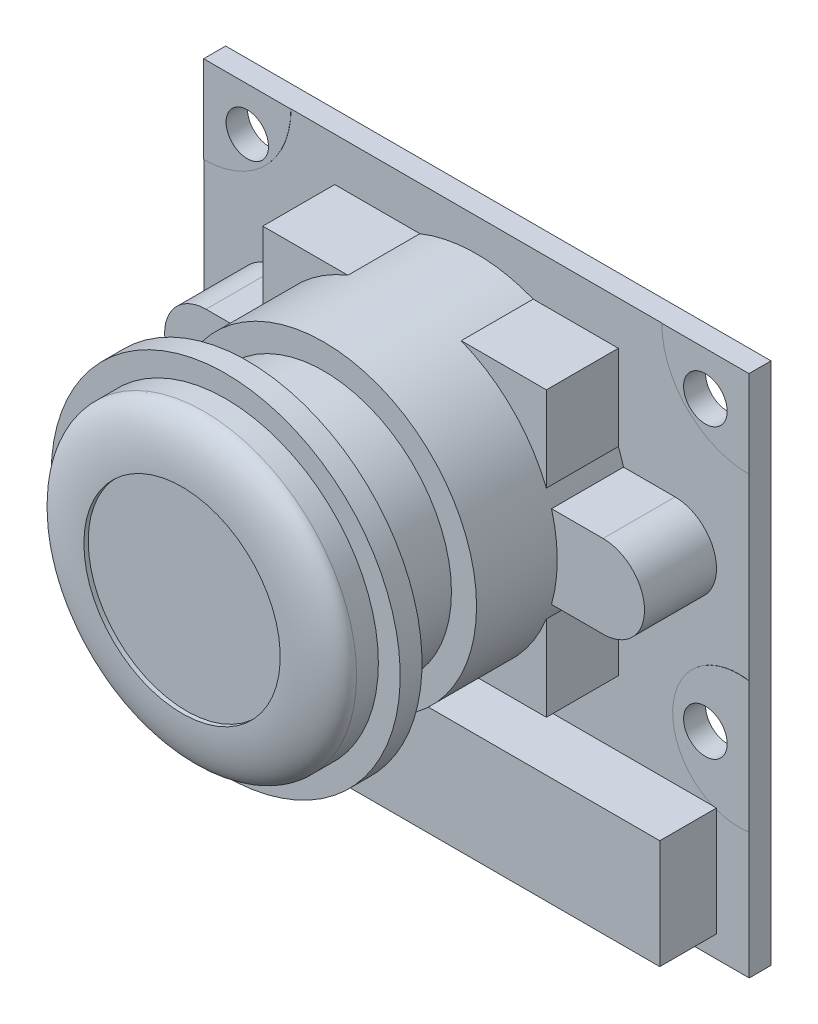
SolidWorks part; units mm, degrees
ref_plane "Alzado" through (0, 0, 0) normal (0, 0, 1) x (1, 0, 0)
ref_plane "Planta" through (0, 0, 0) normal (0, 1, 0) x (1, 0, 0)
ref_plane "Vista lateral" through (0, 0, 0) normal (1, 0, 0) x (0, 0, -1)
sketch "Croquis1" plane through (0, 0, 0) normal (0, 0, 1) x (1, 0, 0)
  line L1 (12.5, 12) -> (-12.5, 12)
  line L2 (12.5, 12) -> (12.5, -12)
  line L3 (12.5, -12) -> (-12.5, -12)
  line L4 (-12.5, 12) -> (-12.5, -12)
  line L5 (12.5, 12) -> (-12.5, -12) construction
  line L6 (12.5, -12) -> (-12.5, 12) construction
  point P0 (0, 0)
  dimension "D1" = 25
  dimension "D2" = 24
extrude "Saliente-Extruir1" add sketch "Croquis1" along normal blind 1
sketch "Croquis2" plane through (0, 0, 1) normal (0, 0, 1) x (1, 0, 0)
  line L0 (-12.5, -12) -> (12.5, -12) construction
  line L1 (11, -6) -> (-11, -6)
  line L2 (11, -6) -> (11, -11)
  line L3 (11, -11) -> (-11, -11)
  line L4 (-11, -6) -> (-11, -11)
  line L5 (11, -6) -> (-11, -11) construction
  line L6 (11, -11) -> (-11, -6) construction
  point P0 (0, -8.5)
  dimension "D1" = 22
  dimension "D2" = 5
  dimension "D3" = 1
extrude "Saliente-Extruir2" add sketch "Croquis2" along normal blind 2.6
sketch "Croquis3" plane through (0, 0, 1) normal (0, 0, 1) x (1, 0, 0)
  line L0 (-9.1, 5.4) -> (-6.5, 5.4)
  line L1 (-6.5, -3) -> (6.5, -3)
  line L2 (-6.5, -3) -> (-6.5, 1.6)
  line L3 (-6.5, 10) -> (6.5, 10)
  line L4 (6.5, -3) -> (6.5, 1.6)
  line L5 (-6.5, -3) -> (6.5, 10) construction
  line L6 (-6.5, 10) -> (6.5, -3) construction
  line L7 (-6.5, 5.4) -> (-6.5, 10)
  line L8 (6.5, 5.4) -> (9.1, 5.4)
  line L9 (6.5, 5.4) -> (6.5, 10)
  line L10 (9.1, 1.6) -> (6.5, 1.6)
  line L11 (12.5, 12) -> (-12.5, 12) construction
  line L12 (-6.5, 1.6) -> (-9.1, 1.6)
  arc A0 (-9.1, 5.4) -> (-9.1, 1.6) centre (-9.1, 3.5) ccw
  arc A1 (9.1, 1.6) -> (9.1, 5.4) centre (9.1, 3.5) ccw
  point P3 (-11, 3.5)
  point P4 (0, 3.5)
  point P19 (11, 3.5)
  dimension "D1" = 22
  dimension "D2" = 3.8
  dimension "D3" = 13
  dimension "D4" = 13
  dimension "D5" = 2
extrude "Saliente-Extruir3" add sketch "Croquis3" along normal blind 3.3
sketch "Croquis5" plane through (0, 0, 1) normal (0, 0, 1) x (1, 0, 0)
  line L0 (-11, 3.5) -> (11, 3.5) construction
  arc A0 (-9.1, 5.4) -> (-9.1, 1.6) centre (-9.1, 3.5) ccw construction
  arc A1 (9.1, 1.6) -> (9.1, 5.4) centre (9.1, 3.5) ccw construction
  circle A2 centre (0, 3.5) radius 7
  dimension "D1" = 14
extrude "Saliente-Extruir4" add sketch "Croquis5" along normal blind 7
sketch "Croquis6" plane through (0, 0, 8) normal (0, 0, 1) x (1, 0, 0)
  circle A0 centre (0, 3.5) radius 5.85
  dimension "D1" = 11.7
extrude "Saliente-Extruir5" add sketch "Croquis6" along normal blind 3.5
sketch "Croquis7" plane through (0, 0, 11.5) normal (0, 0, 1) x (1, 0, 0)
  point P0 (0, 3.5)
ref_plane "Plano1" through (0, 3.5, 0) normal (0, -1, 0) x (-1, 0, 0)
sketch "Croquis8" plane through (0, 3.5, 0) normal (0, -1, 0) x (-1, 0, 0)
  line L0 (0, -11.5) -> (-8, -11.5)
  line L1 (-5.85, -11.5) -> (5.85, -11.5) construction
  line L2 (-8, -11.5) -> (-8, -12.5)
  line L3 (-8, -12.5) -> (-7, -12.5)
  line L4 (-7, -12.5) -> (-7, -13.5)
  line L5 (0, -11.5) -> (0, -14.3)
  line L6 (-4.5, -14.5) -> (-4.5, -14.3)
  line L7 (-4.5, -14.3) -> (0, -14.3)
  ellipse E0 centre (-4.5, -13.5) end of major axis (-7, -13.5) minor radius 1 (-7, -13.5) -> (-4.5, -14.5) ccw
  dimension "D1" = 8
  dimension "D2" = 1
  dimension "D3" = 1
  dimension "D4" = 4.5
  dimension "D5" = 3
  dimension "D6" = 0.2
  dimension "D7" = 1
revolve "Revolución1" add sketch "Croquis8" angle 360 about L5
sketch "Croquis9" plane through (0, 0, 1) normal (0, 0, 1) x (1, 0, 0)
  line L0 (12.5, 12) -> (-12.5, 12) construction
  line L1 (-10.5, 10) -> (10.5, 10) construction
  line L2 (-10.5, 10) -> (-10.5, -3.2) construction
  line L3 (-10.5, -3.2) -> (10.5, -3.2) construction
  line L4 (10.5, 10) -> (10.5, -3.2) construction
  circle A4 centre (-10.5, 10) radius 1
  circle A5 centre (-10.5, -3.2) radius 1
  circle A6 centre (10.5, -3.2) radius 1
  circle A7 centre (10.5, 10) radius 1
  point P8 (0, 10)
  dimension "D1" = 2
  dimension "D2" = 13.2
  dimension "D3" = 21
  dimension "D4" = 2
extrude "Cortar-Extruir1" cut sketch "Croquis9" against normal up to surface (1 mm away) up to face at (0, 0, 0)
sketch "Croquis10" plane through (0, 0, 1) normal (0, 0, 1) x (1, 0, 0)
  line L0 (-12.0357, -3.2) -> (12.0357, -3.2) construction
  line L1 (-12.5, 8) -> (-12.5, 12)
  line L2 (-12.5, 12) -> (-8.5, 12)
  line L3 (-12.5, -0.2) -> (-12.5, -6.2)
  line L4 (8.5, 12) -> (12.5, 12)
  line L5 (12.5, 12) -> (12.5, 8)
  line L7 (12.5, -6.2) -> (12.5, -0.2)
  arc A0 (-12.5, 8) -> (-8.5, 12) centre (-12.5, 12) ccw
  arc A1 (8.5, 12) -> (12.5, 8) centre (12.5, 12) ccw
  arc A2 (12.5, -0.2) -> (12.5, -6.2) centre (12.0357, -3.2) ccw
  arc A3 (-12.5, -6.2) -> (-12.5, -0.2) centre (-12.0357, -3.2) ccw
  circle A4 centre (-10.5, 10) radius 0.9725
  circle A6 centre (10.5, -3.2) radius 1
  circle A7 centre (10.5, 10) radius 1
  circle A8 centre (-10.5, -3.2) radius 1
  circle A9 centre (-10.5, -3.2) radius 1 construction
  point P7 (-9, -3.2)
  point P10 (0, -3.2)
  point P11 (-10.5, -3.2)
  dimension "D1" = 4
  dimension "D2" = 3.5
  dimension "D3" = 6
extrude "Saliente-Extruir6" add sketch "Croquis10" along normal blind 0.01
